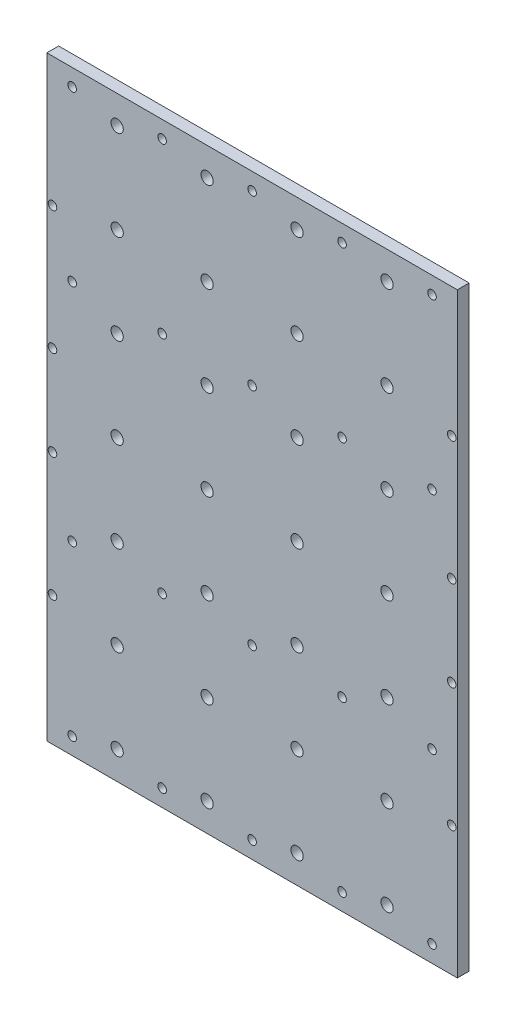
SolidWorks part; units mm, degrees
material "Buche"
ref_plane "Ebene vorne" through (0, 0, 0) normal (0, 0, 1) x (1, 0, 0)
ref_plane "Ebene oben" through (0, 0, 0) normal (0, 1, 0) x (1, 0, 0)
ref_plane "Ebene rechts" through (0, 0, 0) normal (1, 0, 0) x (0, 0, -1)
sketch "Skizze1" plane through (0, 0, 0) normal (0, 0, 1) x (1, 0, 0)
  line L1 (365, 530) -> (-365, 530)
  line L2 (365, 530) -> (365, -530)
  line L3 (365, -530) -> (-365, -530)
  line L4 (-365, 530) -> (-365, -530)
  line L5 (365, 530) -> (-365, -530) construction
  line L6 (365, -530) -> (-365, 530) construction
  point P0 (0, 0)
  dimension "D1" = 730
  dimension "D2" = 1060
extrude "Aufsatz-Linear austragen1" add sketch "Skizze1" along normal blind 21
sketch "Skizze2" plane through (0, 0, 0) normal (0, 0, -1) x (-1, 0, 0)
  line L0 (0, 0) -> (0, -573.4125) construction
  circle A0 centre (80, -480) radius 10.8993
  dimension "D3" = 21.7986
  dimension "D1" = 480
  dimension "D2" = 80
extrude "Schnitt-Linear austragen1" cut sketch "Skizze2" against normal blind 40
sketch "Skizze3" plane through (0, 0, 0) normal (0, 0, -1) x (-1, 0, 0)
  circle A0 centre (80, -480) radius 20.6085
  dimension "D1" = 41.217
extrude "Schnitt-Linear austragen2" cut sketch "Skizze3" against normal blind 5
pattern_linear "Lineares Muster1" count 7 spacing 160 along (0, 1, 0) count 2 spacing 160 along (-1, 0, 0) of "Schnitt-Linear austragen1", "Schnitt-Linear austragen2"
mirror "Spiegeln1" about plane through (0, 0, 0) normal (1, 0, 0) of "Schnitt-Linear austragen1", "Lineares Muster1", "Schnitt-Linear austragen2"
sketch "Skizze4" plane through (0, 0, 21) normal (0, 0, 1) x (1, 0, 0)
  line L0 (0, 0) -> (438.8296, 0) construction
  line L1 (0, 0) -> (0, -564.4828) construction
  line L2 (0, -500) -> (400.6412, -500) construction
  line L3 (-365, -530) -> (365, -530) construction
  line L4 (355, -500) -> (355, 0) construction
  line L5 (365, -530) -> (365, 530) construction
  line L6 (-34.7301, -200) -> (320, -200) construction
  line L7 (160, -500) -> (160, -200) construction
  line L8 (320, -500) -> (320, -200) construction
  line L9 (365, 530) -> (-365, 530) construction
  circle A0 centre (0, -500) radius 7.627
  circle A1 centre (160, -500) radius 7.627
  circle A2 centre (320, -500) radius 7.627
  circle A3 centre (-160, -500) radius 7.627
  circle A4 centre (-320, -500) radius 7.627
  circle A6 centre (355, -300) radius 7.627
  circle A7 centre (355, -80) radius 7.627
  circle A8 centre (-355, -80) radius 7.627
  circle A9 centre (-355, -300) radius 7.627
  circle A11 centre (355, 80) radius 7.627
  circle A12 centre (355, 300) radius 7.627
  circle A14 centre (320, 500) radius 7.627
  circle A15 centre (160, 500) radius 7.627
  circle A16 centre (0, 500) radius 7.627
  circle A18 centre (-355, 300) radius 7.627
  circle A19 centre (-355, 80) radius 7.627
  circle A20 centre (-320, 500) radius 7.627
  circle A21 centre (-160, 500) radius 7.627
  circle A23 centre (160, -200) radius 7.627
  circle A24 centre (320, -200) radius 7.627
  circle A25 centre (0, -200) radius 7.627
  circle A26 centre (-160, -200) radius 7.627
  circle A27 centre (-320, -200) radius 7.627
  circle A28 centre (320, 200) radius 7.627
  circle A29 centre (160, 200) radius 7.627
  circle A30 centre (0, 200) radius 7.627
  circle A31 centre (-160, 200) radius 7.627
  circle A32 centre (-320, 200) radius 7.627
  point P21 (0, 0)
  point P30 (0, 0)
  point P31 (0, 0)
  point P44 (0, 0)
  point P62 (-440.2298, 456.6005)
  point P66 (-34.7301, -180)
  point P67 (0, 0)
  point P82 (0, 0)
  point P83 (0, 0)
  dimension "D2" = 15.254
  dimension "D3" = 160
  dimension "D4" = 160
  dimension "D6" = 330
  dimension "D7" = 220
  dimension "D8" = 330
  dimension "D9" = 230
  dimension "D1" = 30
  dimension "D5" = 10
extrude "Schnitt-Linear austragen3" cut sketch "Skizze4" against normal blind 50
